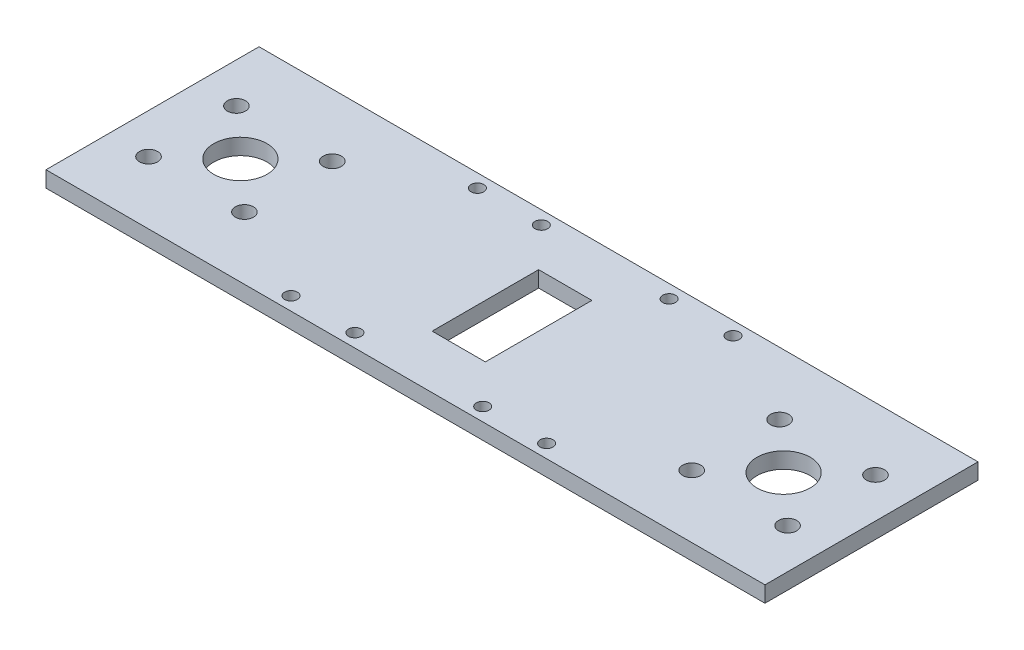
SolidWorks part; units mm, degrees
ref_plane "Front Plane" through (0, 0, 0) normal (0, 0, 1) x (1, 0, 0)
ref_plane "Top Plane" through (0, 0, 0) normal (0, 1, 0) x (1, 0, 0)
ref_plane "Right Plane" through (0, 0, 0) normal (1, 0, 0) x (0, 0, -1)
sketch "Sketch1" plane through (0, 0, 0) normal (0, 1, 0) x (1, 0, 0)
  line L0 (0, 0) -> (0, -14.43) construction
  line L1 (-67.5, 20) -> (67.5, 20)
  line L2 (-67.5, 20) -> (-67.5, -20)
  line L3 (-67.5, -20) -> (67.5, -20)
  line L4 (67.5, 20) -> (67.5, -20)
  line L5 (-67.5, 20) -> (67.5, -20) construction
  line L6 (-67.5, -20) -> (67.5, 20) construction
  line L7 (0, 0) -> (6.9805, 0) construction
  line L8 (-5, 10) -> (5, 10)
  line L9 (-5, 10) -> (-5, -10)
  line L10 (-5, -10) -> (5, -10)
  line L11 (5, 10) -> (5, -10)
  line L12 (-5, 10) -> (5, -10) construction
  line L13 (-5, -10) -> (5, 10) construction
  line L14 (0, 20) -> (0, -20) construction
  circle A0 centre (-51, 0) radius 5
  circle A1 centre (-60, 8.25) radius 1.7
  circle A2 centre (-42, 8.25) radius 1.7
  circle A3 centre (-42, -8.25) radius 1.7
  circle A4 centre (-60, -8.25) radius 1.7
  circle A26 centre (51, 0) radius 5
  circle A27 centre (42, 8.25) radius 1.7
  circle A28 centre (42, -8.25) radius 1.7
  circle A29 centre (60, -8.25) radius 1.7
  circle A30 centre (60, 8.25) radius 1.7
  point P0 (0, 0)
  dimension "D3" = 10
  dimension "D4" = 16.5
  dimension "D5" = 20
  dimension "D6" = 11.75
  dimension "D9" = 10
  dimension "D11" = 7.5
  dimension "D12" = 10
  dimension "D13" = 11.75
  dimension "D10" = 16.5
  dimension "D17" = 18
  dimension "D1" = 135
  dimension "D2" = 40
  dimension "D7" = 2
  dimension "D8" = 2
extrude "Boss-Extrude1" add sketch "Sketch1" along normal blind 3
sketch "Sketch3" plane through (0, 3, 0) normal (0, 1, 0) x (1, 0, 0)
  line L4 (-5, 10) -> (-5, -10) construction
  line L6 (67.5, 20) -> (-67.5, 20) construction
  line L10 (0, 0) -> (0, 13.8836) construction
  circle A1 centre (-12, 17.5) radius 1.2
  circle A2 centre (-12, -17.5) radius 1.2
  circle A4 centre (-24, 17.5) radius 1.2
  circle A5 centre (-24, -17.5) radius 1.2
  circle A8 centre (24, -17.5) radius 1.2
  circle A9 centre (24, 17.5) radius 1.2
  circle A10 centre (12, -17.5) radius 1.2
  circle A11 centre (12, 17.5) radius 1.2
  dimension "D1" = 2.5
  dimension "D2" = 7
  dimension "D3" = 35
  dimension "D5" = 2
  dimension "D6" = 2.4
  dimension "D7" = 2.4
  dimension "D8" = 12
  dimension "D4" = 7
extrude "Cut-Extrude1" cut sketch "Sketch3" against normal blind 10
